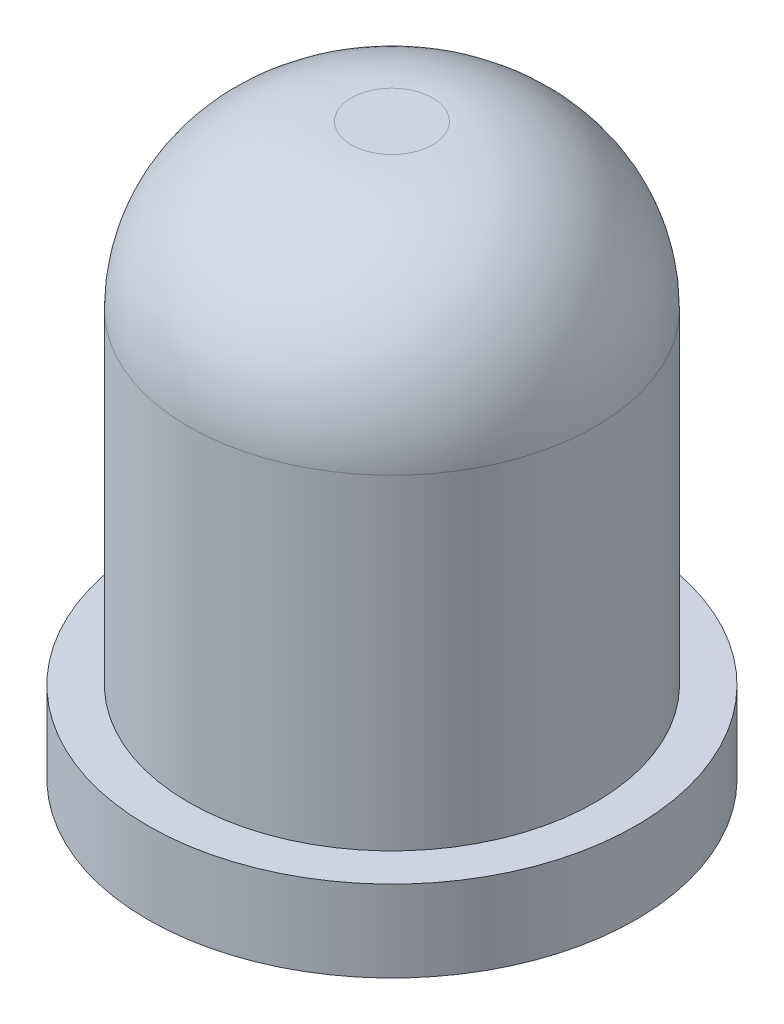
SolidWorks part; units mm, degrees
ref_plane "Front Plane" through (0, 0, 0) normal (0, 0, 1) x (1, 0, 0)
ref_plane "Top Plane" through (0, 0, 0) normal (0, 1, 0) x (1, 0, 0)
ref_plane "Right Plane" through (0, 0, 0) normal (1, 0, 0) x (0, 0, -1)
sketch "Sketch2" plane through (0, 0, 0) normal (0, 1, 0) x (1, 0, 0)
  circle A0 centre (0, 0) radius 3
extrude "Boss-Extrude1" add sketch "Sketch2" along normal blind 1
sketch "Sketch3" plane through (0, 1, 0) normal (0, 1, 0) x (1, 0, 0)
  circle A0 centre (0, 0) radius 2.5
extrude "Boss-Extrude2" add sketch "Sketch3" along normal blind 6
fillet "Fillet1" radius 2 1 edges at (0, 7, 2.5)
